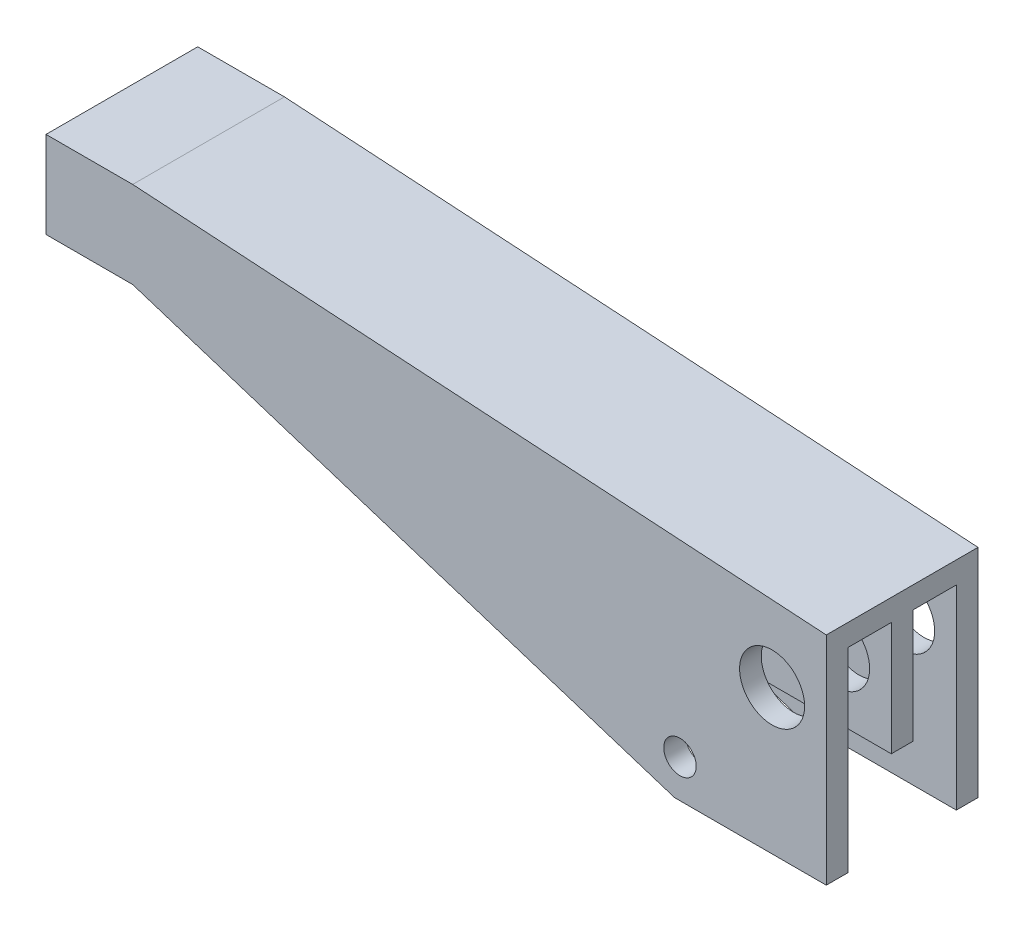
SolidWorks part; units mm, degrees
material "AISI 1045 Steel, cold drawn"
ref_plane "Front Plane" through (0, 0, 0) normal (0, 0, 1) x (1, 0, 0)
ref_plane "Top Plane" through (0, 0, 0) normal (0, 1, 0) x (1, 0, 0)
ref_plane "Right Plane" through (0, 0, 0) normal (1, 0, 0) x (0, 0, -1)
sketch "Sketch1" plane through (0, 0, 0) normal (0, 0, 1) x (1, 0, 0)
  line L0 (-914.4, 304.8) -> (-812.8, 304.8)
  line L1 (-914.4, 304.8) -> (-914.4, 203.2)
  line L2 (-914.4, 203.2) -> (-812.8, 203.2)
  line L4 (-177.8, 0) -> (0, 0)
  line L5 (0, 0) -> (0, 254)
  line L6 (0, 254) -> (-812.8, 304.8)
  line L7 (-812.8, 203.2) -> (-177.8, 0)
  point P6 (-137.0568, 0)
  dimension "D1" = 101.6
  dimension "D2" = 101.6
  dimension "D3" = 914.4
  dimension "D4" = 177.8
  dimension "D6" = 203.2
  dimension "D7" = 254
extrude "Boss-Extrude1" add sketch "Sketch1" against normal blind 25.4
ref_plane "Plane1" through (0, 0, 127) normal (0, 0, 1) x (1, 0, 0)
sketch "Sketch2" plane through (0, 0, 127) normal (0, 0, 1) x (1, 0, 0)
  line L8 (-812.8, 203.2) -> (-177.8, 0)
  line L10 (-177.8, 0) -> (0, 0)
  line L11 (0, 0) -> (0, 254)
  line L12 (0, 254) -> (-812.8, 304.8)
  line L13 (-812.8, 304.8) -> (-914.4, 304.8)
  line L14 (-914.4, 304.8) -> (-914.4, 203.2)
  line L15 (-914.4, 203.2) -> (-812.8, 203.2)
  line L16 (-812.8, 203.2) -> (-177.8, 0)
  line L18 (-177.8, 0) -> (0, 0)
  line L19 (0, 0) -> (0, 254)
  line L20 (0, 254) -> (-812.8, 304.8)
  line L21 (-812.8, 304.8) -> (-914.4, 304.8)
  line L22 (-914.4, 304.8) -> (-914.4, 203.2)
  line L23 (-914.4, 203.2) -> (-812.8, 203.2)
  dimension "D1" = 0
extrude "Boss-Extrude2" add sketch "Sketch2" along normal blind 25.4 separate body
sketch "Sketch3" plane through (0, 0, 152.4) normal (0, 0, 1) x (1, 0, 0)
  line L6 (-914.4, 279.4) -> (-914.4, 304.8)
  line L7 (-914.4, 304.8) -> (-812.8, 304.8)
  line L8 (-812.8, 304.8) -> (0, 254)
  line L9 (-25.4, 0) -> (-25.4, 230.1379)
  line L10 (-25.4, 230.1379) -> (-813.593, 279.4)
  line L11 (-813.593, 279.4) -> (-914.4, 279.4)
  line L12 (-25.4, 230.1379) -> (0, 228.5504)
  line L13 (-25.4, 230.1379) -> (-813.593, 279.4)
  line L14 (-813.593, 279.4) -> (-914.4, 279.4)
  line L15 (0, 0) -> (0, 254) construction
  line L16 (0, 228.5504) -> (0, 254)
  dimension "D1" = 25.4
extrude "Boss-Extrude3" add sketch "Sketch3" against normal up to surface (152.4 mm away) up to face at (-518.8857, 181.4286, 0)
ref_plane "Plane2" through (0, 0, 63.5) normal (0, 0, 1) x (1, 0, 0)
sketch "Sketch6" plane through (0, 0, 63.5) normal (0, 0, 1) x (1, 0, 0)
  line L8 (-812.8, 203.2) -> (-177.8, 0)
  line L10 (-177.8, 0) -> (0, 0)
  line L11 (0, 0) -> (0, 254)
  line L12 (0, 254) -> (-812.8, 304.8)
  line L13 (-812.8, 304.8) -> (-914.4, 304.8)
  line L14 (-914.4, 304.8) -> (-914.4, 203.2)
  line L15 (-914.4, 203.2) -> (-812.8, 203.2)
  line L16 (-812.8, 203.2) -> (-177.8, 0)
  line L18 (-177.8, 0) -> (0, 0)
  line L19 (0, 0) -> (0, 254)
  line L20 (0, 254) -> (-812.8, 304.8)
  line L21 (-812.8, 304.8) -> (-914.4, 304.8)
  line L22 (-914.4, 304.8) -> (-914.4, 203.2)
  line L23 (-914.4, 203.2) -> (-812.8, 203.2)
  dimension "D1" = 0
extrude "Boss-Extrude4" add sketch "Sketch6" along normal blind 12.7 and the other way blind 12.7
sketch "Sketch5" plane through (0, 0, 152.4) normal (0, 0, 1) x (1, 0, 0)
  line L1 (0, 228.5504) -> (-813.593, 279.4) construction
  line L2 (-177.8, 0) -> (0, 0) construction
  line L3 (0, 0) -> (0, 254) construction
  circle A0 centre (-63.5, 168.9696) radius 38.1
  circle A1 centre (-171.45, 44.45) radius 19.05
  point P2 (-25.4, 168.9696)
  point P5 (-63.5, 207.0696)
  point P9 (-171.45, 25.4)
  point P10 (-190.5, 44.45)
  point P13 (-101.6, 168.9696)
  point P14 (0, 0)
  point P17 (-90.297, 38.1)
  point P21 (-152.4, 44.45)
  dimension "D1" = 25.4
  dimension "D3" = 76.2
  dimension "D6" = 38.1
  dimension "D2" = 25.4
  dimension "D4" = 25.4
  dimension "D5" = 50.8
extrude "Cut-Extrude1" cut sketch "Sketch5" against normal through all
sketch "Sketch7" plane through (0, 0, 76.2) normal (0, 0, 1) x (1, 0, 0)
  line L0 (-475.4562, 95.25) -> (0, 95.25)
  line L1 (0, 95.25) -> (0, 0)
  line L2 (0, 0) -> (-177.8, 0)
  line L3 (-177.8, 0) -> (0, 0) construction
  line L4 (0, 0) -> (0, 228.5504) construction
  line L5 (-812.8, 203.2) -> (-177.8, 0) construction
  line L6 (-475.4562, 95.25) -> (-177.8, 0)
  point P3 (-127, 0)
  point P9 (-108.7353, 0)
  dimension "D1" = 95.25
extrude "Cut-Extrude2" cut sketch "Sketch7" against normal up to surface (25.4 mm away) up to face at (-152.4, 44.45, 50.8)
